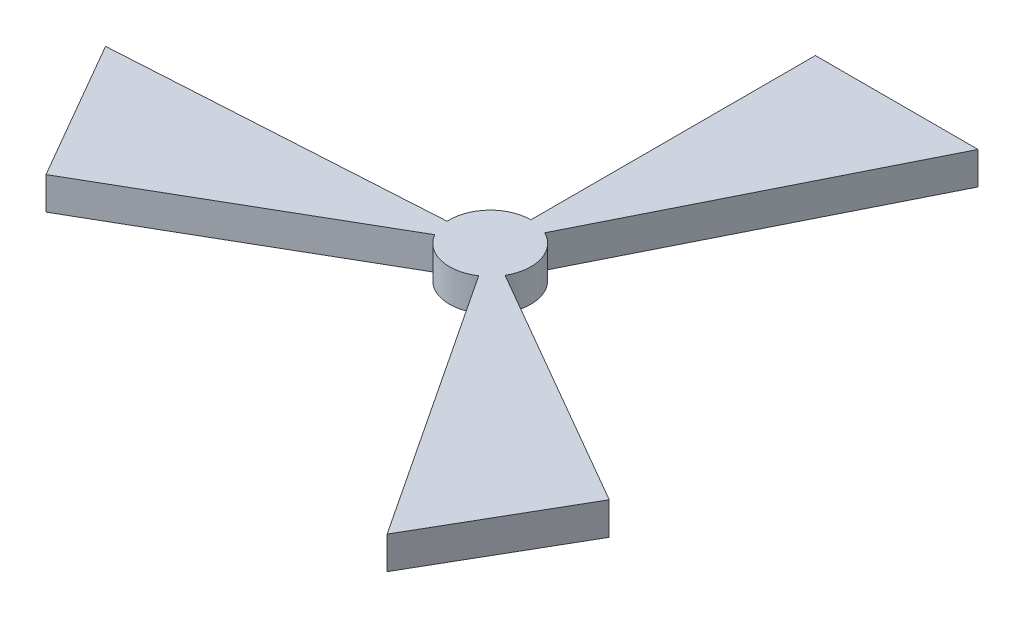
SolidWorks part; units mm, degrees
ref_plane "Front Plane" through (0, 0, 0) normal (0, 0, 1) x (1, 0, 0)
ref_plane "Top Plane" through (0, 0, 0) normal (0, 1, 0) x (1, 0, 0)
ref_plane "Right Plane" through (0, 0, 0) normal (1, 0, 0) x (0, 0, -1)
sketch "Sketch1" plane through (0, 0, 0) normal (0, 1, 0) x (1, 0, 0)
  line L0 (0, 0) -> (0, 100)
  line L1 (0, 100) -> (50, 100)
  line L2 (50, 100) -> (0, 0)
  line L3 (0, 0) -> (86.6025, -50)
  line L4 (86.6025, -50) -> (61.6025, -93.3013)
  line L5 (61.6025, -93.3013) -> (0, 0)
  line L6 (0, 0) -> (-86.6025, -50)
  line L7 (-86.6025, -50) -> (-111.6025, -6.6987)
  line L8 (-111.6025, -6.6987) -> (0, 0)
  circle A0 centre (0, 0) radius 12.5
  dimension "D3" = 25
  dimension "D1" = 100
  dimension "D2" = 50
  dimension "D4" = 120
  dimension "D5" = 240
extrude "Boss-Extrude1" add sketch "Sketch1" along normal blind 10 contours A0 L2 L1 L0 | A0 L8 L7 L6 | A0 L5 L4 L3 | L0 A0 L8 | L2 A0 L0 | L3 A0 L2 | L5 A0 L3 | L6 A0 L5 | L8 A0 L6
